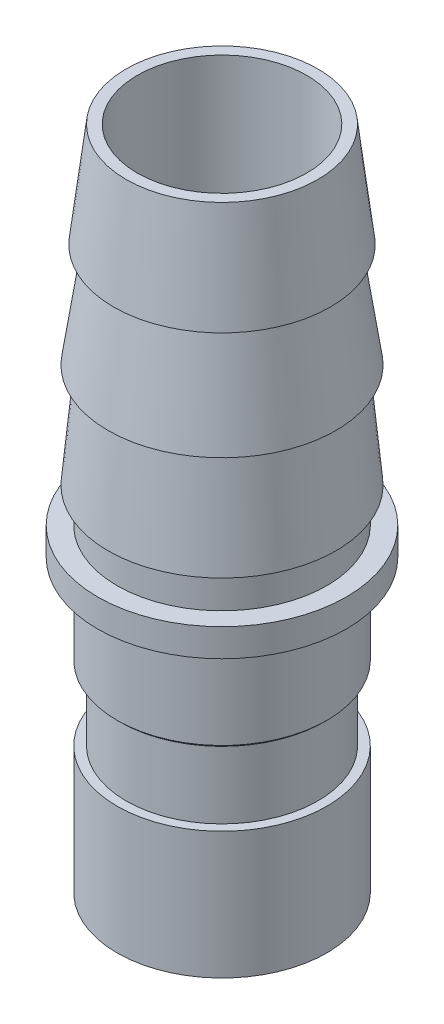
SolidWorks part; units mm, degrees
ref_plane "Front Plane" through (0, 0, 0) normal (0, 0, 1) x (1, 0, 0)
ref_plane "Top Plane" through (0, 0, 0) normal (0, 1, 0) x (1, 0, 0)
ref_plane "Right Plane" through (0, 0, 0) normal (1, 0, 0) x (0, 0, -1)
sketch "Sketch3" plane through (0, 0, 0) normal (0, 0, 1) x (1, 0, 0)
  line L0 (0, 70.3957) -> (0, 0) construction
  line L2 (7.55, 5) -> (7.55, 14.15)
  line L3 (7.55, 14.15) -> (6.9, 14.15)
  line L4 (6.9, 14.15) -> (6.9, 19.3)
  line L5 (6.9, 19.3) -> (7.35, 19.3)
  line L6 (7.55, 19.5) -> (7.55, 25.8957)
  line L14 (0, 0) -> (27.0488, 0) construction
  line L19 (7.35, 19.3) -> (7.55, 19.5)
  line L38 (7.8, 45.3957) -> (7.1, 45.3957)
  line L41 (6.9, 52.8957) -> (7.8, 45.3957)
  line L44 (8.2, 37.8957) -> (7.5, 37.8957)
  line L47 (7.1, 45.3957) -> (8.2, 37.8957)
  line L49 (6.1, 5) -> (7.55, 5)
  line L53 (7.55, 5) -> (0, 5) construction
  line L56 (8.2, 37.8957) -> (8.2, 30.3957) construction
  line L57 (7.55, 30.3957) -> (8.2, 30.3957)
  line L58 (8.2, 30.3957) -> (7.5, 37.8957)
  line L59 (6.9, 52.8957) -> (6.1, 52.8957)
  line L61 (8.95, 27.8957) -> (8.95, 25.8957)
  line L62 (8.95, 25.8957) -> (7.55, 25.8957)
  line L63 (8.95, 27.8957) -> (7.55, 27.8957)
  line L64 (7.55, 27.8957) -> (7.55, 30.3957)
  line L65 (6.1, 5) -> (6.1, 52.8957)
  point P5 (7.55, 19.3)
  dimension "D2" = 0.65
  dimension "D1" = 6.1
  dimension "D3" = 7.55
  dimension "D4" = 0.65
  dimension "D5" = 7.5
  dimension "D6" = 15.1
  dimension "D7" = 5.15
  dimension "D9" = 2
  dimension "D10" = 1.4
  dimension "D11" = 1.4
  dimension "D12" = 2.5
  dimension "D13" = 7.5
  dimension "D14" = 0.65
  dimension "D25" = 0.7
  dimension "D26" = 7.5
  dimension "D27" = 0.7
revolve "Revolve1" add sketch "Sketch3" angle 360 about L0
